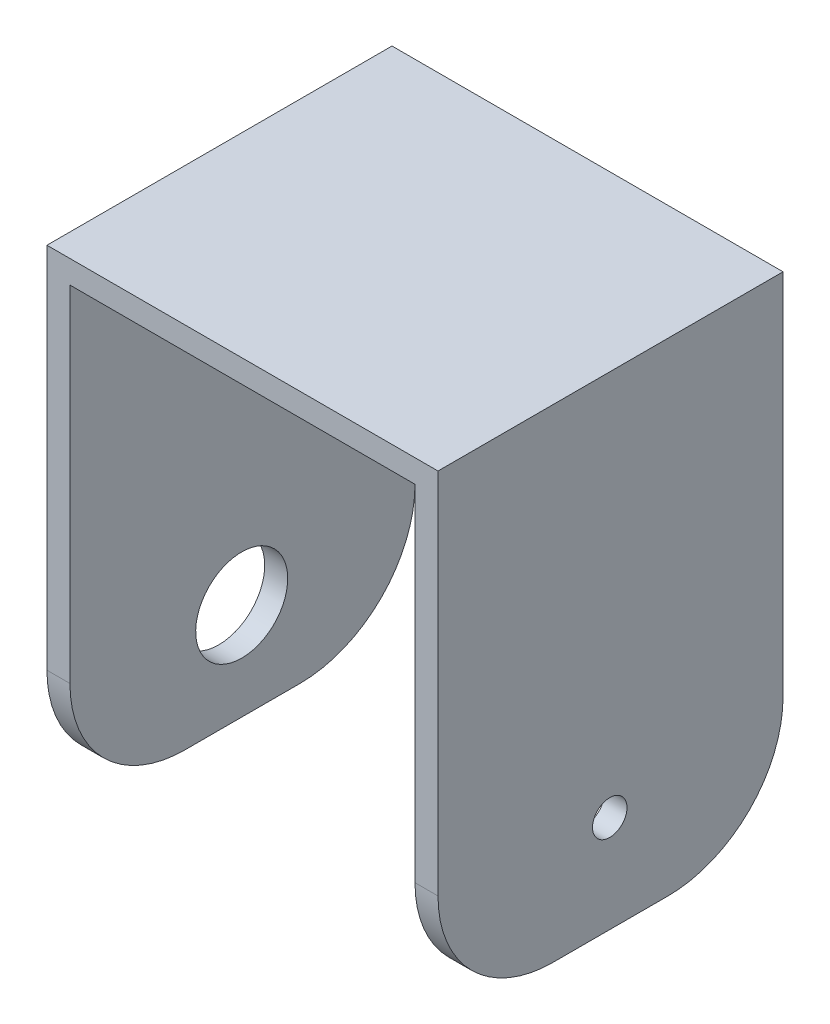
SolidWorks part; units mm, degrees
ref_plane "Front Plane" through (0, 0, 0) normal (0, 0, 1) x (1, 0, 0)
ref_plane "Top Plane" through (0, 0, 0) normal (0, 1, 0) x (1, 0, 0)
ref_plane "Right Plane" through (0, 0, 0) normal (1, 0, 0) x (0, 0, -1)
sketch "Sketch1" plane through (0, 0, 0) normal (0, 0, 1) x (1, 0, 0)
  line L0 (0, 0) -> (0, 40)
  line L1 (0, 40) -> (-30, 40)
  line L2 (-30, 40) -> (-30, 0)
  line L3 (2, 0) -> (2, 42)
  line L4 (2, 42) -> (-32, 42)
  line L5 (-32, 42) -> (-32, 0)
  line L6 (-32, 0) -> (-30, 0)
  line L7 (0, 0) -> (2, 0)
  dimension "D1" = 40
  dimension "D2" = 40
  dimension "D3" = 30
  dimension "D4" = 2
extrude "Boss-Extrude1" add sketch "Sketch1" along normal blind 30
sketch "Sketch2" plane through (-32, 0, 0) normal (-1, 0, 0) x (0, 0, 1)
  line L0 (15, 0) -> (15, 42) construction
  line L1 (30, 0) -> (0, 0) construction
  line L2 (30, 42) -> (0, 42) construction
fillet "Fillet1" radius 10 4 edges at (-31, 0, 30) (1, 0, 30) (1, 0, 0) (-31, 0, 0)
sketch "Sketch4" plane through (-32, 0, 0) normal (-1, 0, 0) x (0, 0, 1)
  circle A0 centre (15.0664, 8.4401) radius 4
  dimension "D1" = 8
extrude "Cut-Extrude1" cut sketch "Sketch4" against normal blind 3
sketch "Sketch5" plane through (2, 0, 0) normal (1, 0, 0) x (0, 0, -1)
  circle A0 centre (-15.0664, 8.4401) radius 1.5
  dimension "D1" = 3
extrude "Cut-Extrude2" cut sketch "Sketch5" against normal blind 3
